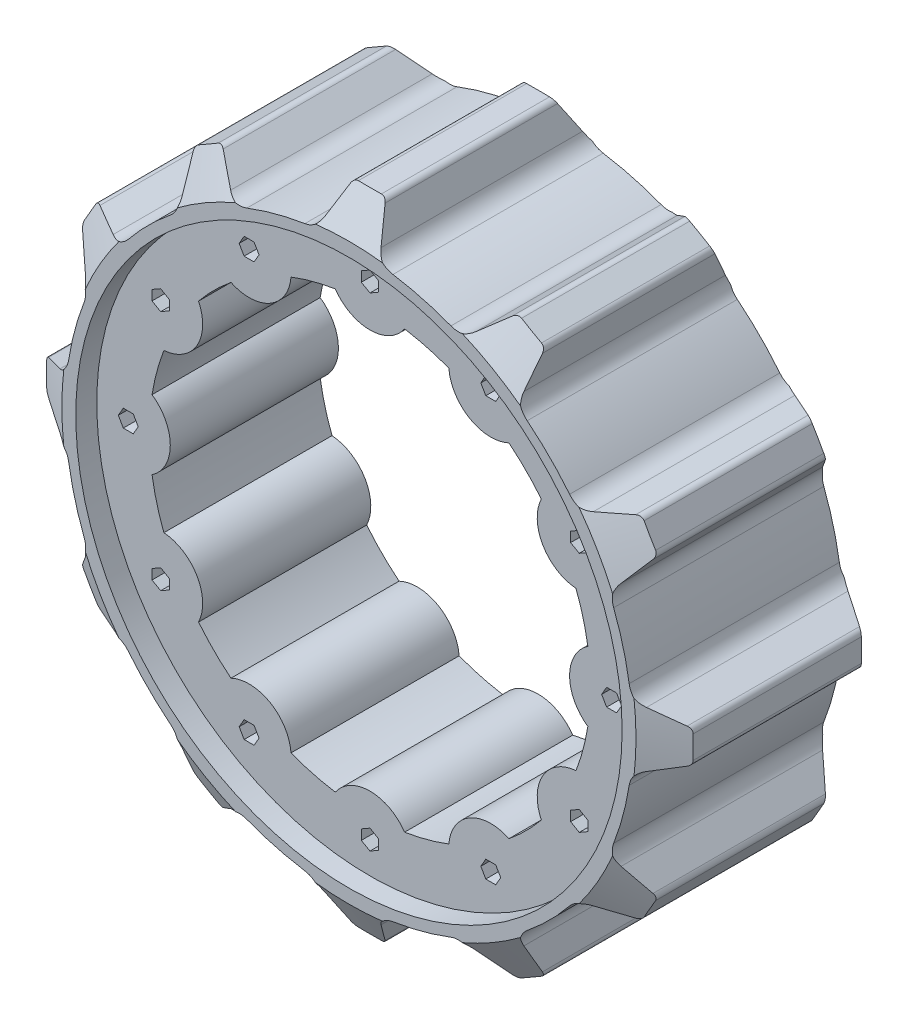
SolidWorks part; units mm, degrees
ref_plane "前视基准面" through (0, 0, 0) normal (0, 0, 1) x (1, 0, 0)
ref_plane "上视基准面" through (0, 0, 0) normal (0, 1, 0) x (1, 0, 0)
ref_plane "右视基准面" through (0, 0, 0) normal (1, 0, 0) x (0, 0, -1)
other "Configuration Table"
sketch "草图1" plane through (0, 0, 0) normal (0, 0, 1) x (1, 0, 0)
  circle A0 centre (0, 0) radius 115 construction
  circle A1 centre (0, 0) radius 105
  circle A2 centre (0, 0) radius 130
  dimension "D1" = 230
  dimension "D2" = 210
  dimension "D3" = 260
extrude "凸台-拉伸1" add sketch "草图1" along normal blind 80
sketch "草图2" plane through (0, 0, 80) normal (0, 0, 1) x (1, 0, 0)
  line L0 (62.2343, 99.5929) -> (59.8671, 103.6929)
  line L1 (4.1, 117.3671) -> (0, 119.7343)
  line L2 (0, 119.7343) -> (-4.1, 117.3671)
  line L3 (-4.1, 117.3671) -> (-4.1, 112.6329)
  line L4 (-4.1, 112.6329) -> (0, 110.2657)
  line L5 (0, 110.2657) -> (4.1, 112.6329)
  line L6 (4.1, 112.6329) -> (4.1, 117.3671)
  line L7 (59.8671, 95.4929) -> (62.2343, 99.5929)
  line L8 (55.1329, 95.4929) -> (59.8671, 95.4929)
  line L9 (52.7657, 99.5929) -> (55.1329, 95.4929)
  line L10 (55.1329, 103.6929) -> (52.7657, 99.5929)
  line L11 (59.8671, 103.6929) -> (55.1329, 103.6929)
  line L12 (103.6929, 55.1329) -> (103.6929, 59.8671)
  line L13 (99.5929, 52.7657) -> (103.6929, 55.1329)
  line L14 (95.4929, 55.1329) -> (99.5929, 52.7657)
  line L15 (95.4929, 59.8671) -> (95.4929, 55.1329)
  line L16 (99.5929, 62.2343) -> (95.4929, 59.8671)
  line L17 (103.6929, 59.8671) -> (99.5929, 62.2343)
  line L18 (117.3671, -4.1) -> (119.7343, 0)
  line L19 (112.6329, -4.1) -> (117.3671, -4.1)
  line L20 (110.2657, 0) -> (112.6329, -4.1)
  line L21 (112.6329, 4.1) -> (110.2657, 0)
  line L22 (117.3671, 4.1) -> (112.6329, 4.1)
  line L23 (119.7343, 0) -> (117.3671, 4.1)
  line L24 (99.5929, -62.2343) -> (103.6929, -59.8671)
  line L25 (95.4929, -59.8671) -> (99.5929, -62.2343)
  line L26 (95.4929, -55.1329) -> (95.4929, -59.8671)
  line L27 (99.5929, -52.7657) -> (95.4929, -55.1329)
  line L28 (103.6929, -55.1329) -> (99.5929, -52.7657)
  line L29 (103.6929, -59.8671) -> (103.6929, -55.1329)
  line L30 (55.1329, -103.6929) -> (59.8671, -103.6929)
  line L31 (52.7657, -99.5929) -> (55.1329, -103.6929)
  line L32 (55.1329, -95.4929) -> (52.7657, -99.5929)
  line L33 (59.8671, -95.4929) -> (55.1329, -95.4929)
  line L34 (62.2343, -99.5929) -> (59.8671, -95.4929)
  line L35 (59.8671, -103.6929) -> (62.2343, -99.5929)
  line L36 (-4.1, -117.3671) -> (0, -119.7343)
  line L37 (-4.1, -112.6329) -> (-4.1, -117.3671)
  line L38 (0, -110.2657) -> (-4.1, -112.6329)
  line L39 (4.1, -112.6329) -> (0, -110.2657)
  line L40 (4.1, -117.3671) -> (4.1, -112.6329)
  line L41 (0, -119.7343) -> (4.1, -117.3671)
  line L42 (-62.2343, -99.5929) -> (-59.8671, -103.6929)
  line L43 (-59.8671, -95.4929) -> (-62.2343, -99.5929)
  line L44 (-55.1329, -95.4929) -> (-59.8671, -95.4929)
  line L45 (-52.7657, -99.5929) -> (-55.1329, -95.4929)
  line L46 (-55.1329, -103.6929) -> (-52.7657, -99.5929)
  line L47 (-59.8671, -103.6929) -> (-55.1329, -103.6929)
  line L48 (-103.6929, -55.1329) -> (-103.6929, -59.8671)
  line L49 (-99.5929, -52.7657) -> (-103.6929, -55.1329)
  line L50 (-95.4929, -55.1329) -> (-99.5929, -52.7657)
  line L51 (-95.4929, -59.8671) -> (-95.4929, -55.1329)
  line L52 (-99.5929, -62.2343) -> (-95.4929, -59.8671)
  line L53 (-103.6929, -59.8671) -> (-99.5929, -62.2343)
  line L54 (-117.3671, 4.1) -> (-119.7343, 0)
  line L55 (-112.6329, 4.1) -> (-117.3671, 4.1)
  line L56 (-110.2657, 0) -> (-112.6329, 4.1)
  line L57 (-112.6329, -4.1) -> (-110.2657, 0)
  line L58 (-117.3671, -4.1) -> (-112.6329, -4.1)
  line L59 (-119.7343, 0) -> (-117.3671, -4.1)
  line L60 (-99.5929, 62.2343) -> (-103.6929, 59.8671)
  line L61 (-95.4929, 59.8671) -> (-99.5929, 62.2343)
  line L62 (-95.4929, 55.1329) -> (-95.4929, 59.8671)
  line L63 (-99.5929, 52.7657) -> (-95.4929, 55.1329)
  line L64 (-103.6929, 55.1329) -> (-99.5929, 52.7657)
  line L65 (-103.6929, 59.8671) -> (-103.6929, 55.1329)
  line L66 (-55.1329, 103.6929) -> (-59.8671, 103.6929)
  line L67 (-52.7657, 99.5929) -> (-55.1329, 103.6929)
  line L68 (-55.1329, 95.4929) -> (-52.7657, 99.5929)
  line L69 (-59.8671, 95.4929) -> (-55.1329, 95.4929)
  line L70 (-62.2343, 99.5929) -> (-59.8671, 95.4929)
  line L71 (-59.8671, 103.6929) -> (-62.2343, 99.5929)
  circle A0 centre (0, 0) radius 115 construction
  circle A1 centre (0, 115) radius 2.5 construction
  circle A2 centre (0, 115) radius 4.1 construction
  point P80 (0, 0)
  dimension "D1" = 230
  dimension "D2" = 5
  dimension "D3" = 4.7343
  dimension "D4" = 8.2
  dimension "D5" = 12
extrude "切除-拉伸1" cut sketch "草图2" against normal through all
sketch "草图5" plane through (0, 0, 80) normal (0, 0, 1) x (1, 0, 0)
  circle A0 centre (0, 0) radius 130
  circle A1 centre (0, 0) radius 150
  dimension "D1" = 260
  dimension "D2" = 300
extrude "凸台-拉伸2" add sketch "草图5" against normal blind 90 and the other way blind 10
sketch "草图7" plane through (0, 0, 80) normal (0, 0, 1) x (1, 0, 0)
  line L0 (0, 119.7343) -> (0, 110.2657) construction
  line L1 (0, 110.2657) -> (4.1, 112.6329) construction
  line L2 (-20, 115) -> (-7.5, 115)
  line L3 (7.5, 115) -> (20, 115)
  line L4 (40.1795, 109.5929) -> (51.0048, 103.3429)
  line L5 (63.9952, 95.8429) -> (74.8205, 89.5929)
  line L6 (89.5929, 74.8205) -> (95.8429, 63.9952)
  line L7 (103.3429, 51.0048) -> (109.5929, 40.1795)
  line L8 (115, 20) -> (115, 7.5)
  line L9 (115, -7.5) -> (115, -20)
  line L10 (109.5929, -40.1795) -> (103.3429, -51.0048)
  line L11 (95.8429, -63.9952) -> (89.5929, -74.8205)
  line L12 (74.8205, -89.5929) -> (63.9952, -95.8429)
  line L13 (51.0048, -103.3429) -> (40.1795, -109.5929)
  line L14 (20, -115) -> (7.5, -115)
  line L15 (-7.5, -115) -> (-20, -115)
  line L16 (-40.1795, -109.5929) -> (-51.0048, -103.3429)
  line L17 (-63.9952, -95.8429) -> (-74.8205, -89.5929)
  line L18 (-89.5929, -74.8205) -> (-95.8429, -63.9952)
  line L19 (-103.3429, -51.0048) -> (-109.5929, -40.1795)
  line L20 (-115, -20) -> (-115, -7.5)
  line L21 (-115, 7.5) -> (-115, 20)
  line L22 (-109.5929, 40.1795) -> (-103.3429, 51.0048)
  line L23 (-95.8429, 63.9952) -> (-89.5929, 74.8205)
  line L24 (-74.8205, 89.5929) -> (-63.9952, 95.8429)
  line L25 (-51.0048, 103.3429) -> (-40.1795, 109.5929)
  arc A0 (-7.5, 115) -> (7.5, 115) centre (0, 115) ccw
  arc A1 (-20, 115) -> (20, 115) centre (0, 115) ccw
  arc A2 (51.0048, 103.3429) -> (63.9952, 95.8429) centre (57.5, 99.5929) ccw
  arc A3 (40.1795, 109.5929) -> (74.8205, 89.5929) centre (57.5, 99.5929) ccw
  arc A4 (95.8429, 63.9952) -> (103.3429, 51.0048) centre (99.5929, 57.5) ccw
  arc A5 (89.5929, 74.8205) -> (109.5929, 40.1795) centre (99.5929, 57.5) ccw
  arc A6 (115, 7.5) -> (115, -7.5) centre (115, 0) ccw
  arc A7 (115, 20) -> (115, -20) centre (115, 0) ccw
  arc A8 (103.3429, -51.0048) -> (95.8429, -63.9952) centre (99.5929, -57.5) ccw
  arc A9 (109.5929, -40.1795) -> (89.5929, -74.8205) centre (99.5929, -57.5) ccw
  arc A10 (63.9952, -95.8429) -> (51.0048, -103.3429) centre (57.5, -99.5929) ccw
  arc A11 (74.8205, -89.5929) -> (40.1795, -109.5929) centre (57.5, -99.5929) ccw
  arc A12 (7.5, -115) -> (-7.5, -115) centre (0, -115) ccw
  arc A13 (20, -115) -> (-20, -115) centre (0, -115) ccw
  arc A14 (-51.0048, -103.3429) -> (-63.9952, -95.8429) centre (-57.5, -99.5929) ccw
  arc A15 (-40.1795, -109.5929) -> (-74.8205, -89.5929) centre (-57.5, -99.5929) ccw
  arc A16 (-95.8429, -63.9952) -> (-103.3429, -51.0048) centre (-99.5929, -57.5) ccw
  arc A17 (-89.5929, -74.8205) -> (-109.5929, -40.1795) centre (-99.5929, -57.5) ccw
  arc A18 (-115, -7.5) -> (-115, 7.5) centre (-115, 0) ccw
  arc A19 (-115, -20) -> (-115, 20) centre (-115, 0) ccw
  arc A20 (-103.3429, 51.0048) -> (-95.8429, 63.9952) centre (-99.5929, 57.5) ccw
  arc A21 (-109.5929, 40.1795) -> (-89.5929, 74.8205) centre (-99.5929, 57.5) ccw
  arc A22 (-63.9952, 95.8429) -> (-51.0048, 103.3429) centre (-57.5, 99.5929) ccw
  arc A23 (-74.8205, 89.5929) -> (-40.1795, 109.5929) centre (-57.5, 99.5929) ccw
  point P69 (0, 0)
  dimension "D1" = 15
  dimension "D2" = 40
  dimension "D3" = 12
extrude "凸台-拉伸3" add sketch "草图7" against normal blind 80
sketch "草图8" plane through (0, 0, 90) normal (0, 0, 1) x (1, 0, 0)
  line L0 (-7.5, 153.8167) -> (7.5, 153.8167)
  line L1 (7.5, 153.8167) -> (17.5, 128.8167)
  line L2 (-7.5, 153.8167) -> (-17.5, 128.8167)
  line L3 (-17.5, 128.8167) -> (17.5, 128.8167)
  line L4 (0, 153.8167) -> (0, 128.8167) construction
  line L5 (0, 128.8167) -> (0, 0)
  line L6 (70.4132, 136.9592) -> (83.4036, 129.4592)
  line L7 (70.4132, 136.9592) -> (49.2529, 120.3086)
  line L8 (83.4036, 129.4592) -> (79.5638, 102.8086)
  line L9 (49.2529, 120.3086) -> (79.5638, 102.8086)
  line L10 (129.4592, 83.4036) -> (136.9592, 70.4132)
  line L11 (129.4592, 83.4036) -> (102.8086, 79.5638)
  line L12 (136.9592, 70.4132) -> (120.3086, 49.2529)
  line L13 (102.8086, 79.5638) -> (120.3086, 49.2529)
  line L14 (153.8167, 7.5) -> (153.8167, -7.5)
  line L15 (153.8167, 7.5) -> (128.8167, 17.5)
  line L16 (153.8167, -7.5) -> (128.8167, -17.5)
  line L17 (128.8167, 17.5) -> (128.8167, -17.5)
  line L18 (136.9592, -70.4132) -> (129.4592, -83.4036)
  line L19 (136.9592, -70.4132) -> (120.3086, -49.2529)
  line L20 (129.4592, -83.4036) -> (102.8086, -79.5638)
  line L21 (120.3086, -49.2529) -> (102.8086, -79.5638)
  line L22 (83.4036, -129.4592) -> (70.4132, -136.9592)
  line L23 (83.4036, -129.4592) -> (79.5638, -102.8086)
  line L24 (70.4132, -136.9592) -> (49.2529, -120.3086)
  line L25 (79.5638, -102.8086) -> (49.2529, -120.3086)
  line L26 (7.5, -153.8167) -> (-7.5, -153.8167)
  line L27 (7.5, -153.8167) -> (17.5, -128.8167)
  line L28 (-7.5, -153.8167) -> (-17.5, -128.8167)
  line L29 (17.5, -128.8167) -> (-17.5, -128.8167)
  line L30 (-70.4132, -136.9592) -> (-83.4036, -129.4592)
  line L31 (-70.4132, -136.9592) -> (-49.2529, -120.3086)
  line L32 (-83.4036, -129.4592) -> (-79.5638, -102.8086)
  line L33 (-49.2529, -120.3086) -> (-79.5638, -102.8086)
  line L34 (-129.4592, -83.4036) -> (-136.9592, -70.4132)
  line L35 (-129.4592, -83.4036) -> (-102.8086, -79.5638)
  line L36 (-136.9592, -70.4132) -> (-120.3086, -49.2529)
  line L37 (-102.8086, -79.5638) -> (-120.3086, -49.2529)
  line L38 (-153.8167, -7.5) -> (-153.8167, 7.5)
  line L39 (-153.8167, -7.5) -> (-128.8167, -17.5)
  line L40 (-153.8167, 7.5) -> (-128.8167, 17.5)
  line L41 (-128.8167, -17.5) -> (-128.8167, 17.5)
  line L42 (-136.9592, 70.4132) -> (-129.4592, 83.4036)
  line L43 (-136.9592, 70.4132) -> (-120.3086, 49.2529)
  line L44 (-129.4592, 83.4036) -> (-102.8086, 79.5638)
  line L45 (-120.3086, 49.2529) -> (-102.8086, 79.5638)
  line L46 (-83.4036, 129.4592) -> (-70.4132, 136.9592)
  line L47 (-83.4036, 129.4592) -> (-79.5638, 102.8086)
  line L48 (-70.4132, 136.9592) -> (-49.2529, 120.3086)
  line L49 (-79.5638, 102.8086) -> (-49.2529, 120.3086)
  circle A1 centre (0, 0) radius 130 construction
  circle A2 centre (0, 0) radius 130 construction
  point P59 (0, 0)
  point P91 (0, 0)
  dimension "D1" = 15
  dimension "D2" = 35
  dimension "D3" = 128.8167
  dimension "D4" = 25
  dimension "D5" = 12
extrude "凸台-拉伸4" add sketch "草图8" against normal through all
sketch "草图10" plane through (0, 0, 90) normal (0, 0, 1) x (1, 0, 0)
  line L0 (-9.1381, 149.7214) -> (-15.3782, 134.1213)
  line L1 (9.1381, 149.7214) -> (15.3782, 134.1213)
  line L2 (-7.5, 153.8167) -> (-9.1381, 149.7214) construction
  line L3 (7.5, 153.8167) -> (9.1381, 149.7214) construction
  line L4 (66.9468, 134.2316) -> (53.7427, 123.8415)
  line L5 (82.7746, 125.0935) -> (80.3785, 108.4633)
  line L6 (125.0935, 82.7746) -> (108.4633, 80.3785)
  line L7 (134.2316, 66.9468) -> (123.8415, 53.7427)
  line L8 (149.7214, 9.1381) -> (134.1213, 15.3782)
  line L9 (149.7214, -9.1381) -> (134.1213, -15.3782)
  line L10 (134.2316, -66.9468) -> (123.8415, -53.7427)
  line L11 (125.0935, -82.7746) -> (108.4633, -80.3785)
  line L12 (82.7746, -125.0935) -> (80.3785, -108.4633)
  line L13 (66.9468, -134.2316) -> (53.7427, -123.8415)
  line L14 (9.1381, -149.7214) -> (15.3782, -134.1213)
  line L15 (-9.1381, -149.7214) -> (-15.3782, -134.1213)
  line L16 (-66.9468, -134.2316) -> (-53.7427, -123.8415)
  line L17 (-82.7746, -125.0935) -> (-80.3785, -108.4633)
  line L18 (-125.0935, -82.7746) -> (-108.4633, -80.3785)
  line L19 (-134.2316, -66.9468) -> (-123.8415, -53.7427)
  line L20 (-149.7214, -9.1381) -> (-134.1213, -15.3782)
  line L21 (-149.7214, 9.1381) -> (-134.1213, 15.3782)
  line L22 (-134.2316, 66.9468) -> (-123.8415, 53.7427)
  line L23 (-125.0935, 82.7746) -> (-108.4633, 80.3785)
  line L24 (-82.7746, 125.0935) -> (-80.3785, 108.4633)
  line L25 (-66.9468, 134.2316) -> (-53.7427, 123.8415)
  arc A0 (-123.8415, 53.7427) -> (-134.1213, 15.3782) centre (0, 0) ccw
  arc A1 (-134.1213, -15.3782) -> (-123.8415, -53.7427) centre (0, 0) ccw
  arc A14 (-82.7746, 125.0935) -> (-125.0935, 82.7746) centre (0, 0) ccw
  arc A15 (-134.2316, 66.9468) -> (-149.7214, 9.1381) centre (0, 0) ccw
  arc A16 (-149.7214, -9.1381) -> (-134.2316, -66.9468) centre (0, 0) ccw
  arc A17 (-125.0935, -82.7746) -> (-82.7746, -125.0935) centre (0, 0) ccw
  arc A18 (-66.9468, -134.2316) -> (-9.1381, -149.7214) centre (0, 0) ccw
  arc A19 (9.1381, -149.7214) -> (66.9468, -134.2316) centre (0, 0) ccw
  arc A20 (82.7746, -125.0935) -> (125.0935, -82.7746) centre (0, 0) ccw
  arc A21 (134.2316, -66.9468) -> (149.7214, -9.1381) centre (0, 0) ccw
  arc A22 (149.7214, 9.1381) -> (134.2316, 66.9468) centre (0, 0) ccw
  arc A23 (125.0935, 82.7746) -> (82.7746, 125.0935) centre (0, 0) ccw
  arc A24 (66.9468, 134.2316) -> (9.1381, 149.7214) centre (0, 0) ccw
  arc A25 (-9.1381, 149.7214) -> (-66.9468, 134.2316) centre (0, 0) ccw
  arc A26 (53.7427, 123.8415) -> (15.3782, 134.1213) centre (0, 0) ccw
  arc A27 (-15.3782, 134.1213) -> (-53.7427, 123.8415) centre (0, 0) ccw
  arc A28 (-80.3785, 108.4633) -> (-108.4633, 80.3785) centre (0, 0) ccw
  arc A29 (-108.4633, -80.3785) -> (-80.3785, -108.4633) centre (0, 0) ccw
  arc A30 (-53.7427, -123.8415) -> (-15.3782, -134.1213) centre (0, 0) ccw
  arc A31 (15.3782, -134.1213) -> (53.7427, -123.8415) centre (0, 0) ccw
  arc A32 (80.3785, -108.4633) -> (108.4633, -80.3785) centre (0, 0) ccw
  arc A33 (123.8415, -53.7427) -> (134.1213, -15.3782) centre (0, 0) ccw
  arc A34 (134.1213, 15.3782) -> (123.8415, 53.7427) centre (0, 0) ccw
  arc A35 (108.4633, 80.3785) -> (80.3785, 108.4633) centre (0, 0) ccw
  point P61 (0, 0)
  dimension "D2" = 270
  dimension "D1" = 12
extrude "切除-拉伸4" cut sketch "草图10" against normal through all
fillet "圆角2" radius 10 24 edges at (-134.1213, -15.3782, 40) (-123.8415, -53.7427, 40) (-108.4633, -80.3785, 40) (-80.3785, -108.4633, 40) (-53.7427, -123.8415, 40) (-15.3782, -134.1213, 40) (15.3782, -134.1213, 40) (53.7427, -123.8415, 40) (80.3785, -108.4633, 40) (108.4633, -80.3785, 40) (123.8415, -53.7427, 40) (134.1213, -15.3782, 40) (134.1213, 15.3782, 40) (123.8415, 53.7427, 40) (80.3785, 108.4633, 40) (108.4633, 80.3785, 40) (-134.1213, 15.3782, 40) (-123.8415, 53.7427, 40) (53.7427, 123.8415, 40) (15.3782, 134.1213, 40) (-108.4633, 80.3785, 40) (-80.3785, 108.4633, 40) (-15.3782, 134.1213, 40) (-53.7427, 123.8415, 40)
fillet "圆角3" radius 3 24 edges at (70.4132, -136.9592, 40) (83.4036, -129.4592, 40) (129.4592, -83.4036, 40) (136.9592, -70.4132, 40) (153.8167, -7.5, 40) (153.8167, 7.5, 40) (136.9592, 70.4132, 40) (129.4592, 83.4036, 40) (83.4036, 129.4592, 40) (70.4132, 136.9592, 40) (7.5, 153.8167, 40) (-70.4132, 136.9592, 40) (-83.4036, 129.4592, 40) (-129.4592, 83.4036, 40) (-136.9592, 70.4132, 40) (-153.8167, 7.5, 40) (-153.8167, -7.5, 40) (-136.9592, -70.4132, 40) (-129.4592, -83.4036, 40) (-83.4036, -129.4592, 40) (-70.4132, -136.9592, 40) (-7.5, -153.8167, 40) (7.5, -153.8167, 40) (-7.5, 153.8167, 40)
sketch "草图11" plane through (0, 0, 0) normal (0, 1, 0) x (1, 0, 0)
  line L0 (0, 0) -> (0, 60) construction
  line L1 (-153.8167, -40) -> (153.8167, -40) construction
  line L3 (-50, 60) -> (-160, -3.5085)
  line L4 (-153.8167, -90) -> (-153.8167, 10) construction
  line L5 (153.8167, 10) -> (153.8167, -90) construction
  line L7 (-160, -140) -> (-160, -76.4915)
  line L8 (-50, 60) -> (-160, 60)
  line L9 (-160, 60) -> (-160, -3.5085)
  line L10 (-50, -140) -> (-160, -140)
  line L11 (-50, -140) -> (-160, -76.4915)
  dimension "D1" = 60
  dimension "D2" = 30
  dimension "D3" = 100
  dimension "D4" = 320
revolve "切除-旋转4" cut sketch "草图11" angle 360 about L0
